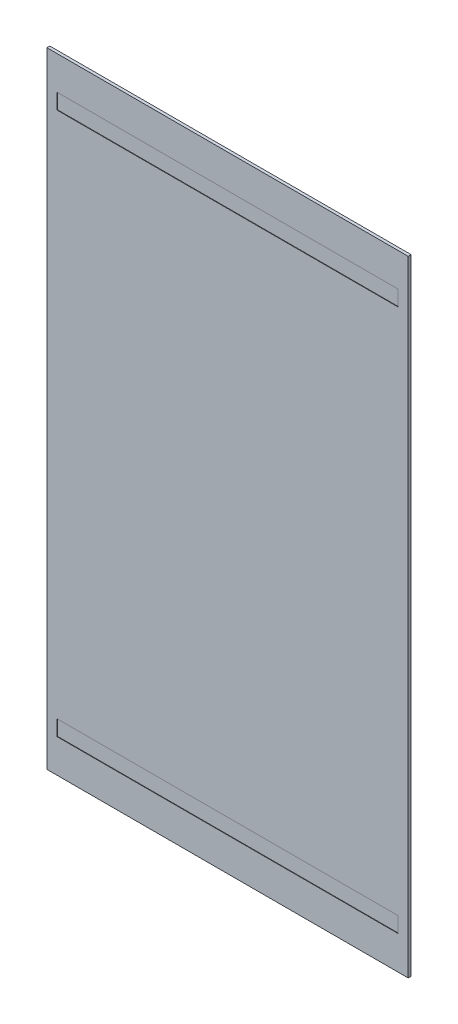
SolidWorks part; units mm, degrees
ref_plane "Front" through (0, 0, 0) normal (0, 0, 1) x (1, 0, 0)
ref_plane "Top" through (0, 0, 0) normal (0, 1, 0) x (1, 0, 0)
ref_plane "Right" through (0, 0, 0) normal (1, 0, 0) x (0, 0, -1)
sketch "Sketch1" plane through (0, 0, 0) normal (0, 0, 1) x (1, 0, 0)
  line L5 (-18.5, 32) -> (18.5, 32)
  line L6 (-18.5, 32) -> (-18.5, -32)
  line L7 (-18.5, -32) -> (18.5, -32)
  line L8 (18.5, 32) -> (18.5, -32)
extrude "Extrude1" add sketch "Sketch1" along normal blind 0.3
sketch "Sketch2" plane through (0, 0, 0.3) normal (0, 0, 1) x (1, 0, 0)
  line L2 (-17.4625, 28.575) -> (17.4625, 28.575)
  line L3 (-17.4625, 28.575) -> (-17.4625, 26.9875)
  line L4 (-17.4625, 26.9875) -> (17.4625, 26.9875)
  line L5 (-17.4625, -26.9875) -> (17.4625, -26.9875)
  line L6 (-17.4625, -26.9875) -> (-17.4625, -28.575)
  line L7 (-17.4625, -28.575) -> (17.4625, -28.575)
  line L8 (17.4625, -26.9875) -> (17.4625, -28.575)
  line L9 (17.4625, 28.575) -> (17.4625, 26.9875)
extrude "Cut-Extrude1" cut sketch "Sketch2" against normal blind 0.05
